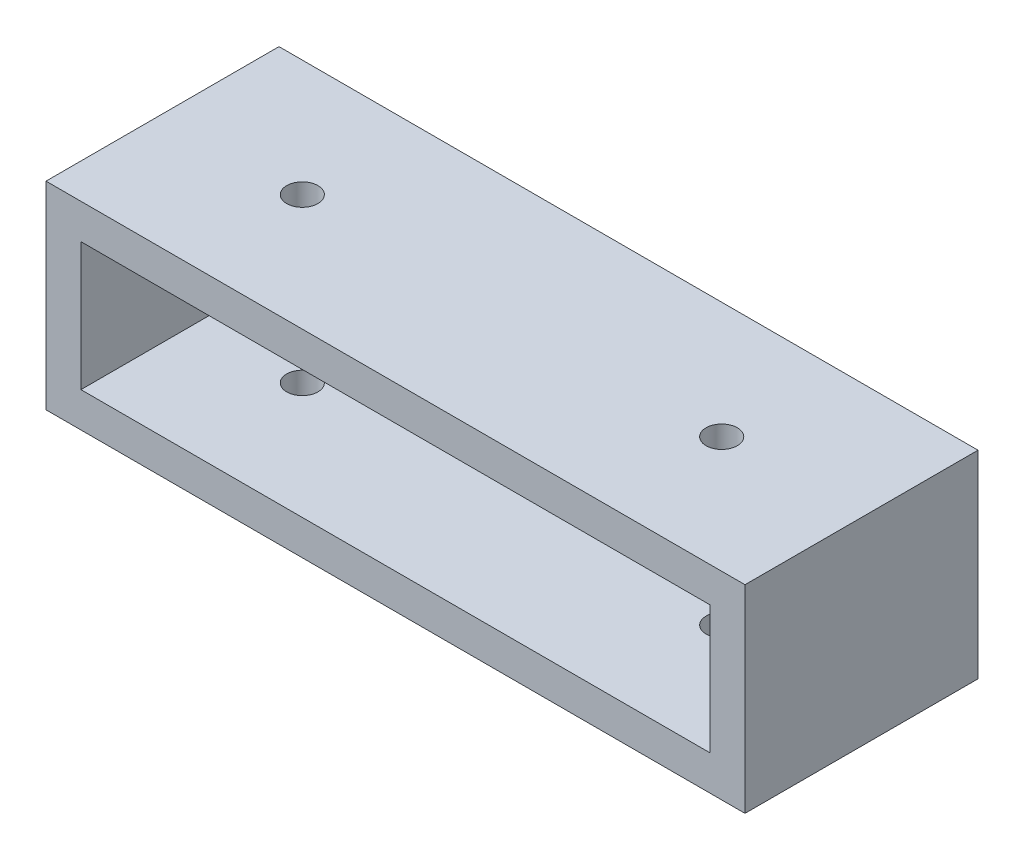
SolidWorks part; units mm, degrees
ref_plane "Front Plane" through (0, 0, 0) normal (0, 0, 1) x (1, 0, 0)
ref_plane "Top Plane" through (0, 0, 0) normal (0, 1, 0) x (1, 0, 0)
ref_plane "Right Plane" through (0, 0, 0) normal (1, 0, 0) x (0, 0, -1)
sketch "Sketch1" plane through (0, 0, 0) normal (0, 1, 0) x (1, 0, 0)
  line L1 (-75, 25) -> (75, 25)
  line L2 (-75, 25) -> (-75, -25)
  line L3 (-75, -25) -> (75, -25)
  line L4 (75, 25) -> (75, -25)
  line L5 (-75, 25) -> (75, -25) construction
  line L6 (-75, -25) -> (75, 25) construction
  point P0 (0, 0)
  dimension "D1" = 150
  dimension "D2" = 50
extrude "Boss-Extrude1" add sketch "Sketch1" along normal blind 7.5
sketch "Sketch2" plane through (0, 7.5, 0) normal (0, 1, 0) x (1, 0, 0)
  line L0 (-75, 0) -> (75, 0) construction
  line L1 (-75, 25) -> (-75, -25) construction
  line L2 (75, -25) -> (75, 25) construction
  circle A0 centre (-45, 0) radius 3.35
  circle A1 centre (45, 0) radius 3.35
  dimension "D1" = 30
  dimension "D2" = 30
extrude "Cut-Extrude1" cut sketch "Sketch2" against normal blind 7.5
sketch "Sketch3" plane through (0, 0, 0) normal (0, -1, 0) x (1, 0, 0)
  line L0 (75, -25) -> (-75, -25) construction
  line L1 (-75, 25) -> (-60, 25)
  line L2 (-75, 25) -> (-75, -25)
  line L3 (-75, -25) -> (-60, -25)
  line L4 (-60, 25) -> (-60, -25)
  line L6 (75, 25) -> (60, 25)
  line L7 (75, 25) -> (75, -25)
  line L8 (75, -25) -> (60, -25)
  line L9 (60, 25) -> (60, -25)
  dimension "D1" = 15
  dimension "D2" = 15
extrude "Boss-Extrude2" add sketch "Sketch3" along normal blind 35
sketch "Sketch6" plane through (-60, 0, 0) normal (1, 0, 0) x (0, 0, -1)
  line L0 (25, -35) -> (25, 0) construction
  line L1 (-25, -35) -> (25, -35)
  line L2 (-25, -35) -> (-25, -27.5)
  line L3 (-25, -27.5) -> (25, -27.5)
  line L4 (25, -35) -> (25, -27.5)
  dimension "D1" = 7.5
extrude "Boss-Extrude5" add sketch "Sketch6" along normal blind 120
sketch "Sketch10" plane through (0, -27.5, 0) normal (0, 1, 0) x (1, 0, 0)
  line L0 (-60, 0) -> (60, 0) construction
  line L1 (-60, 25) -> (-60, -25) construction
  line L2 (60, 25) -> (60, -25) construction
  circle A0 centre (-45, 0) radius 3.35
  circle A1 centre (45, 0) radius 3.35
  dimension "D1" = 15
  dimension "D2" = 15
extrude "Cut-Extrude4" cut sketch "Sketch10" against normal blind 7.5
sketch "Sketch11" plane through (-60, 0, 0) normal (1, 0, 0) x (0, 0, -1)
  line L1 (-25, 0) -> (25, 0)
  line L2 (-25, 0) -> (-25, -27.5)
  line L3 (-25, -27.5) -> (25, -27.5)
  line L4 (25, 0) -> (25, -27.5)
extrude "Cut-Extrude5" cut sketch "Sketch11" against normal blind 7.5
sketch "Sketch12" plane through (60, 0, 0) normal (-1, 0, 0) x (0, 0, 1)
  line L1 (-25, 0) -> (25, 0)
  line L2 (-25, 0) -> (-25, -27.5)
  line L3 (-25, -27.5) -> (25, -27.5)
  line L4 (25, 0) -> (25, -27.5)
extrude "Cut-Extrude6" cut sketch "Sketch12" against normal blind 7.5
